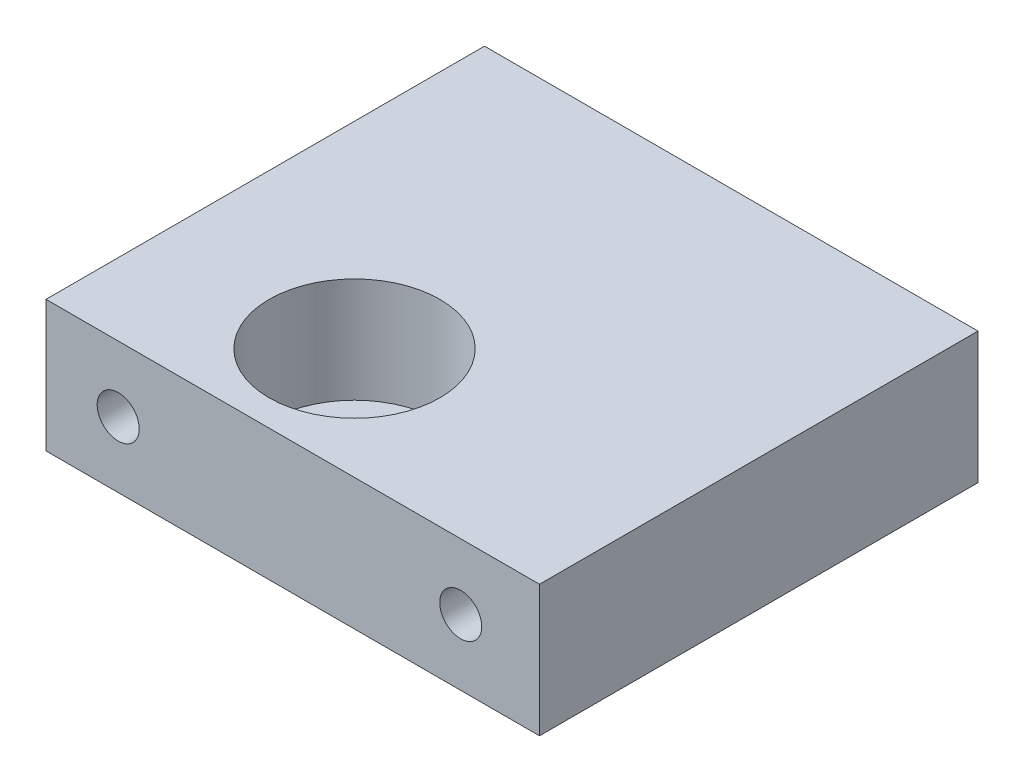
SolidWorks part; units mm, degrees
ref_plane "Front Plane" through (0, 0, 0) normal (0, 0, 1) x (1, 0, 0)
ref_plane "Top Plane" through (0, 0, 0) normal (0, 1, 0) x (1, 0, 0)
ref_plane "Right Plane" through (0, 0, 0) normal (1, 0, 0) x (0, 0, -1)
sketch "Sketch1" plane through (0, 0, 0) normal (0, 0, 1) x (1, 0, 0)
  line L1 (-8.7886, 15.5842) -> (28.8006, 15.5842)
  line L2 (-8.7886, 15.5842) -> (-8.7886, 5.5842)
  line L3 (-8.7886, 5.5842) -> (28.8006, 5.5842)
  line L4 (28.8006, 15.5842) -> (28.8006, 5.5842)
  line L5 (-8.7886, 15.5842) -> (28.8006, 5.5842) construction
  line L6 (-8.7886, 5.5842) -> (28.8006, 15.5842) construction
  point P0 (10.006, 10.5842)
  dimension "D1" = 10
  dimension "D2" = 37.5893
extrude "Boss-Extrude1" add sketch "Sketch1" along normal blind 33.4 contours L3 L4 L1 L2
sketch "Sketch2" plane through (0, 15.5842, 0) normal (0, 1, 0) x (1, 0, 0)
  line L0 (-8.7886, -33.4) -> (28.8006, -33.4) construction
  line L1 (-8.7886, -33.4) -> (-8.7886, 0) construction
  circle A0 centre (6.2114, -24.9) radius 6.5
  dimension "D1" = 13
  dimension "D2" = 8.5
  dimension "D3" = 15
extrude "Cut-Extrude1" cut sketch "Sketch2" against normal blind 10
sketch "Sketch3" plane through (0, 0, 33.4) normal (0, 0, 1) x (1, 0, 0)
  line L0 (-8.7886, 15.5842) -> (28.8006, 15.5842) construction
  line L1 (-8.7886, 15.5842) -> (-8.7886, 5.5842) construction
  line L2 (28.8006, 15.5842) -> (28.8006, 5.5842) construction
  circle A0 centre (-3.2886, 10.5842) radius 1.6
  circle A1 centre (22.8006, 10.5842) radius 1.6
  dimension "D1" = 3.2
  dimension "D4" = 3.2
  dimension "D2" = 5
  dimension "D3" = 5.5
  dimension "D5" = 6
  dimension "D6" = 5
extrude "Cut-Extrude3" cut sketch "Sketch3" along normal blind 40 from surface at -33.4 starting at face at (10.006, 10.5842, 0)
sketch "Sketch4" plane through (0, 5.5842, 0) normal (0, -1, 0) x (1, 0, 0)
  circle A0 centre (6.2114, 24.9) radius 6.6
  circle A1 centre (6.2114, 24.9) radius 2.75
  dimension "D1" = 5.5
  dimension "D2" = 13.2
extrude "Boss-Extrude2" add sketch "Sketch4" against normal blind 2
